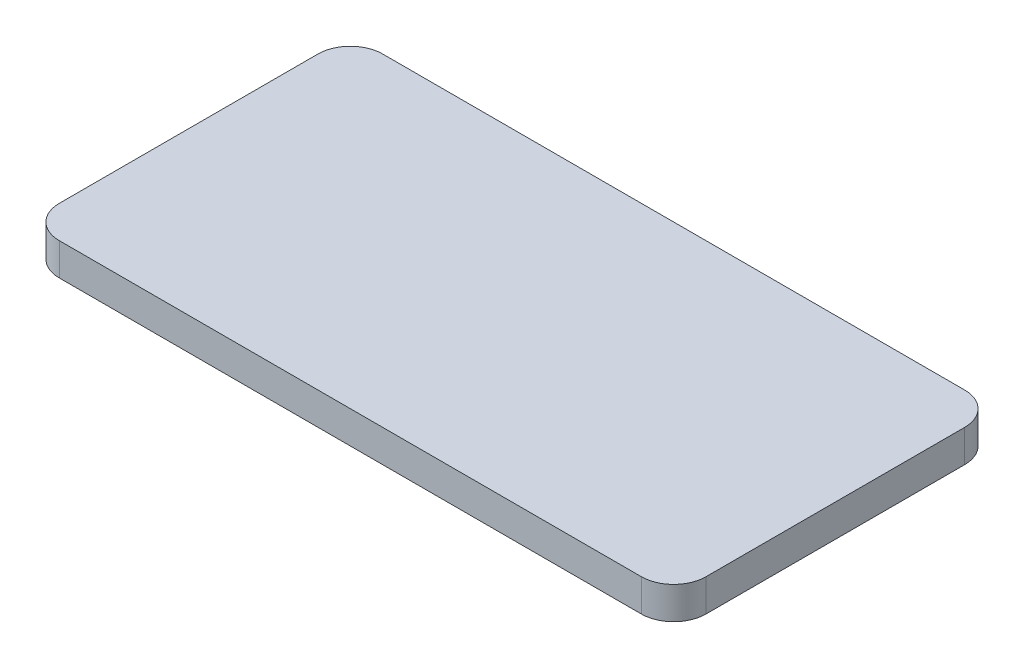
SolidWorks part; units mm, degrees
ref_plane "Front Plane" through (0, 0, 0) normal (0, 0, 1) x (1, 0, 0)
ref_plane "Top Plane" through (0, 0, 0) normal (0, 1, 0) x (1, 0, 0)
ref_plane "Right Plane" through (0, 0, 0) normal (1, 0, 0) x (0, 0, -1)
sketch "Sketch1" plane through (0, 0, 0) normal (0, 1, 0) x (1, 0, 0)
  line L0 (-50, 0) -> (50, 0) construction
  line L1 (-45, -25) -> (45, -25)
  line L2 (-45, 25) -> (45, 25)
  line L3 (-50, -20) -> (-50, 20)
  line L4 (50, -20) -> (50, 20)
  line L5 (-50, 25) -> (50, 25) construction
  line L6 (-50, -25) -> (50, -25) construction
  arc A0 (45, 25) -> (50, 20) centre (45, 20) cw
  arc A1 (50, -20) -> (45, -25) centre (45, -20) cw
  arc A2 (-45, -25) -> (-50, -20) centre (-45, -20) cw
  arc A3 (-50, 20) -> (-45, 25) centre (-45, 20) cw
  dimension "D4" = 5
  dimension "D1" = 100
  dimension "D2" = 25
  dimension "D3" = 25
extrude "Boss-Extrude1" add sketch "Sketch1" along normal blind 5
sketch "Sketch2" plane through (0, 0, 0) normal (0, -1, 0) x (-1, 0, 0)
  line L5 (45, -25) -> (-45, -25) construction
  line L6 (-50, -20) -> (-50, 20) construction
  line L7 (-43.7077, -20) -> (-30.7077, -20)
  line L8 (-44.7077, -19) -> (-44.7077, -6)
  line L9 (-43.7077, -5) -> (-30.7077, -5)
  line L10 (-29.7077, -19) -> (-29.7077, -6)
  line L11 (-44.7077, -20) -> (-29.7077, -5) construction
  line L12 (-44.7077, -5) -> (-29.7077, -20) construction
  arc A0 (-29.7077, -19) -> (-30.7077, -20) centre (-30.7077, -19) cw
  arc A1 (-29.7077, -6) -> (-30.7077, -5) centre (-30.7077, -6) ccw
  arc A2 (-44.7077, -6) -> (-43.7077, -5) centre (-43.7077, -6) cw
  arc A3 (-44.7077, -19) -> (-43.7077, -20) centre (-43.7077, -19) ccw
  point P5 (-37.2077, -12.5)
  point P12 (0, 0)
  dimension "D5" = 1
  dimension "D1" = 5
  dimension "D2" = 5.2923
  dimension "D3" = 15
  dimension "D4" = 15
extrude "Cut-Extrude1" cut sketch "Sketch2" against normal blind 1
sketch "Sketch3" plane through (0, 1, 0) normal (0, -1, 0) x (-1, 0, 0)
  circle A0 centre (-37.9149, -8.7559) radius 3.5
  circle A2 centre (-34.0246, -14.8428) radius 3.5
  circle A4 centre (-41.2094, -15.2612) radius 3.5
  dimension "D1" = 7
  dimension "D2" = 7
  dimension "D3" = 7
extrude "Boss-Extrude2" add sketch "Sketch3" along normal blind 2
sketch "Sketch4" plane through (-50, 0, 0) normal (-1, 0, 0) x (0, 0, 1)
  line L0 (20, 5) -> (20, 0) construction
  line L1 (2, 1.7705) -> (-2, 1.7705)
  line L2 (2.5, 2.2705) -> (2.5, 3.2705)
  line L3 (2, 3.7705) -> (-2, 3.7705)
  line L4 (-2.5, 2.2705) -> (-2.5, 3.2705)
  line L5 (2.5, 1.7705) -> (-2.5, 3.7705) construction
  line L6 (2.5, 3.7705) -> (-2.5, 1.7705) construction
  arc A0 (-2, 1.7705) -> (-2.5, 2.2705) centre (-2, 2.2705) cw
  arc A1 (-2.5, 3.2705) -> (-2, 3.7705) centre (-2, 3.2705) cw
  arc A2 (2.5, 3.2705) -> (2, 3.7705) centre (2, 3.2705) ccw
  arc A3 (2, 1.7705) -> (2.5, 2.2705) centre (2, 2.2705) ccw
  point P0 (0, 2.7705)
  point P5 (0, 0)
  point P6 (0, 2.3985)
  point P7 (0, 0)
  point P8 (0, 0)
  point P9 (0, 0)
  point P10 (0, 0)
  point P11 (0, 0)
  point P12 (0, 0)
  point P13 (-1.0096, 2.4517)
  point P14 (0, 0)
  point P15 (-0.372, 3.1956)
  point P16 (0, 0)
  point P17 (0, 0)
  point P18 (0, 0)
  point P19 (0, 0)
  point P20 (0, 0)
  point P21 (0, 0)
  point P22 (0, 0)
  point P23 (0, 0)
  point P24 (0, 0)
  point P39 (20, 2.5)
  point P40 (2.5, 2.7705)
  dimension "D3" = 0.5
  dimension "D1" = 2
  dimension "D2" = 5
  dimension "D4" = 17.5
extrude "Cut-Extrude2" cut sketch "Sketch4" against normal blind 5
